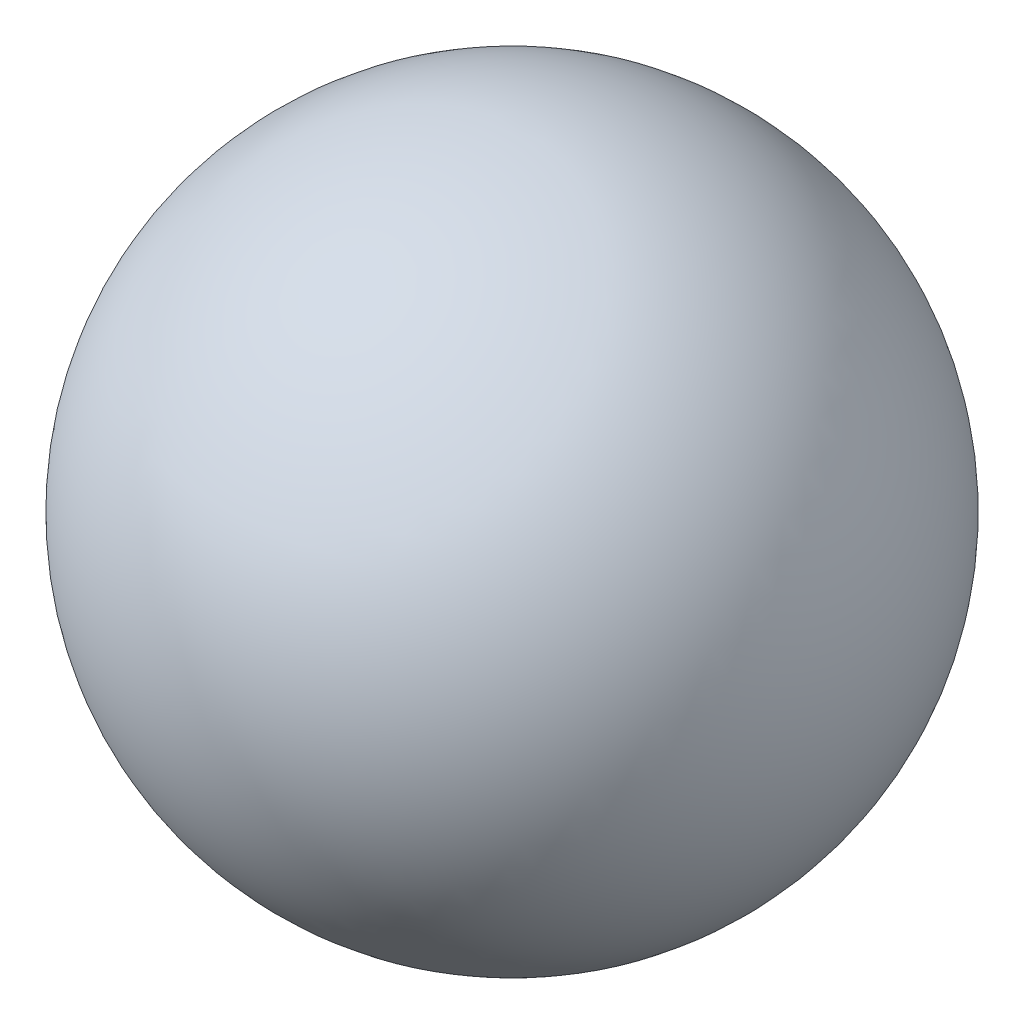
SolidWorks part; units mm, degrees
ref_plane "Front Plane" through (0, 0, 0) normal (0, 0, 1) x (1, 0, 0)
ref_plane "Top Plane" through (0, 0, 0) normal (0, 1, 0) x (1, 0, 0)
ref_plane "Right Plane" through (0, 0, 0) normal (1, 0, 0) x (0, 0, -1)
sketch "Sketch1" plane through (0, 0, 0) normal (0, 0, 1) x (1, 0, 0)
  line L0 (0, 45) -> (0, 42)
  line L1 (0, -42) -> (0, -45)
  arc A1 (0, 45) -> (0, -45) centre (0, 0) cw
  arc A2 (0, 42) -> (0, -42) centre (0, 0) cw
  dimension "D1" = 45
  dimension "D2" = 42
revolve "Revolve2" add sketch "Sketch1" angle 360 about L0
